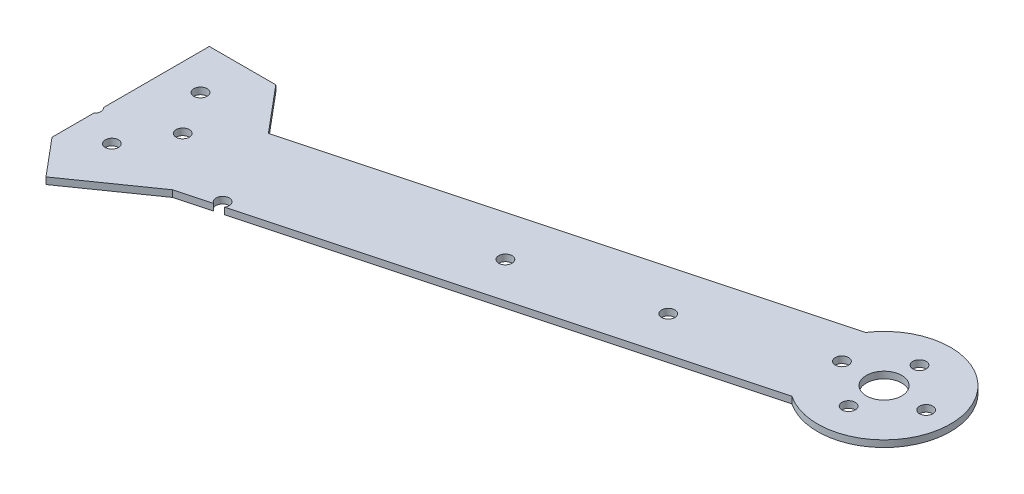
SolidWorks part; units mm, degrees
other "Markup1"
sketch "Sketch5" plane through (0, 1.5, 8.4265) normal (-0.2691, 0.6708, 0.6911) x (0.9345, 0.0084, 0.3557)
ref_plane "Front Plane" through (0, 0, 0) normal (0, 0, 1) x (1, 0, 0)
ref_plane "Top Plane" through (0, 0, 0) normal (0, 1, 0) x (1, 0, 0)
ref_plane "Right Plane" through (0, 0, 0) normal (1, 0, 0) x (0, 0, -1)
sketch "Sketch2" plane through (0, 0, 0) normal (0, 1, 0) x (1, 0, 0)
  line L0 (0, 0) -> (0, 9.382)
  line L1 (0, 35.5) -> (15, 35.5)
  line L2 (15, 35.5) -> (23.6776, 25.1584)
  line L3 (23.6776, 25.1584) -> (129.9295, 53.6285)
  line L4 (0, 0) -> (7.0707, -8.4265)
  line L5 (7.0707, -8.4265) -> (23.8633, 3.3318)
  line L6 (23.8633, 3.3318) -> (134.0979, 32.8636)
  line L7 (23.6776, 25.1584) -> (23.8633, 3.3318) construction
  line L8 (136.0028, 45.3369) -> (147.7774, 45.3369) construction
  line L9 (147.7774, 45.3369) -> (142.4295, 45.3369) construction
  line L10 (142.4295, 45.3369) -> (142.4295, 51.3946) construction
  line L11 (142.4295, 45.3369) -> (142.4295, 39.9998)
  line L24 (0, 11.618) -> (0, 35.5)
  arc A0 (134.0979, 32.8636) -> (129.9295, 53.6285) centre (142.4295, 45.3369) ccw
  circle A1 centre (142.4295, 45.3369) radius 4
  circle A10 centre (8, 25.5) radius 1.5
  circle A11 centre (14, 15.5) radius 1.5
  circle A12 centre (8, 5.5) radius 1.5
  arc A13 (0, 9.382) -> (0, 11.618) centre (-1, 10.5) ccw
  circle A14 centre (142.4295, 53.3369) radius 1.5
  circle A15 centre (151.9295, 45.3369) radius 1.5
  circle A16 centre (142.4295, 37.3369) radius 1.5
  circle A17 centre (132.9295, 45.3369) radius 1.5
  point P46 (142.4295, 45.3369)
  dimension "D8" = 16
  dimension "D16" = 8
  dimension "D17" = 8
  dimension "D21" = 8
  dimension "D22" = 3
  dimension "D23" = 10
  dimension "D24" = 14
  dimension "D25" = 3
  dimension "D26" = 20
  dimension "D27" = 3
  dimension "D28" = 30
  dimension "D29" = 3
  dimension "D30" = 15
  dimension "D18" = 19
  dimension "D19" = 9.5
  dimension "D1" = 35.5
  dimension "D2" = 15
  dimension "D3" = 13.5
  dimension "D4" = 130
  dimension "D5" = 110
  dimension "D6" = 115
  dimension "D7" = 12.5
  dimension "D9" = 15
  dimension "D10" = 11
  dimension "D11" = 140
  dimension "D12" = 95
  dimension "D13" = 20.5
  dimension "D14" = 75.49
  dimension "D15" = 104.513
  dimension "D31" = 15
extrude "Boss-Extrude1" add sketch "Sketch2" along normal blind 1.5
sketch "Sketch3" plane through (0, 1.5, 0) normal (0, 1, 0) x (1, 0, 0)
  circle A0 centre (31.86, 6.64) radius 1.5
  circle A1 centre (14, 15.5) radius 1.5 construction
  dimension "D1" = 3
  dimension "D2" = 17.86
  dimension "D3" = 8.86
extrude "Cut-Extrude1" cut sketch "Sketch3" against normal up to surface (1.5 mm away) up to face at (132.9295, 0, -43.8369)
sketch "Sketch4" plane through (0, 1.5, 0) normal (0, 1, 0) x (1, 0, 0)
  line L0 (142.4295, 45.3369) -> (23.572, 13.4892) construction
  line L1 (23.6776, 25.1584) -> (129.9295, 53.6285) construction
  circle A0 centre (75.0373, 27.2793) radius 1.5
  circle A1 centre (104.0151, 35.0438) radius 1.5
  dimension "D1" = 30
  dimension "D2" = 3
  dimension "D3" = 3
extrude "Cut-Extrude2" cut sketch "Sketch4" against normal up to surface (1.5 mm away) up to face at (132.9295, 0, -43.8369)
